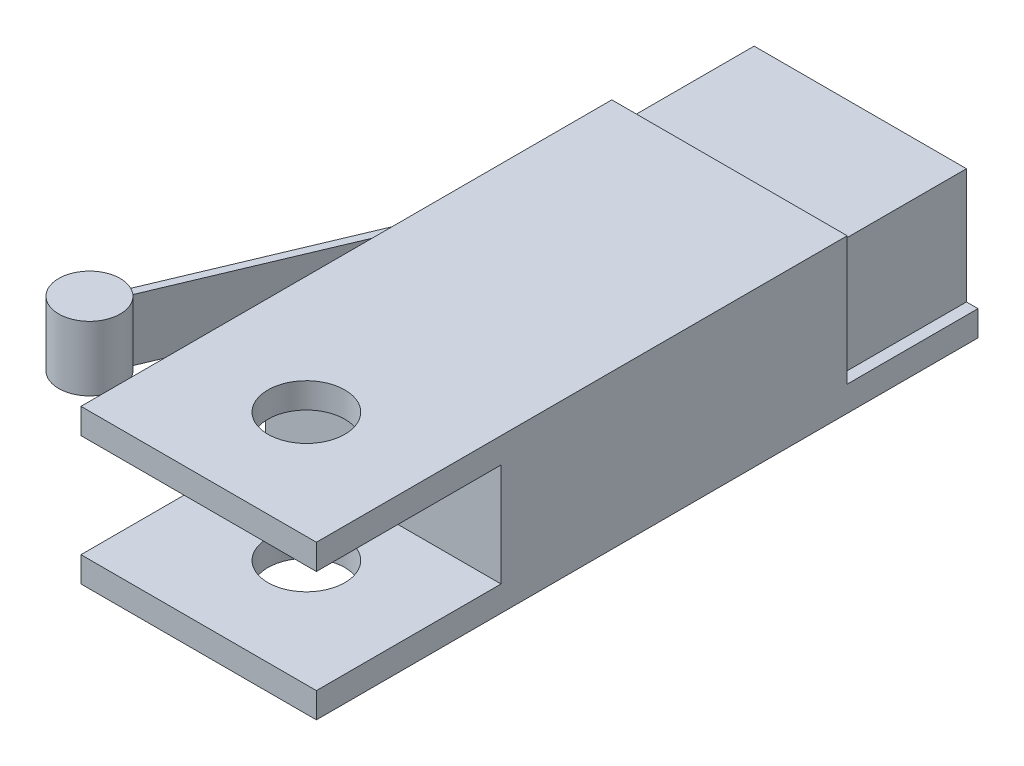
SolidWorks part; units mm, degrees
ref_plane "Front Plane" through (0, 0, 0) normal (0, 0, 1) x (1, 0, 0)
ref_plane "Top Plane" through (0, 0, 0) normal (0, 1, 0) x (1, 0, 0)
ref_plane "Right Plane" through (0, 0, 0) normal (1, 0, 0) x (0, 0, -1)
sketch "Sketch1" plane through (0, 0, 0) normal (0, 1, 0) x (1, 0, 0)
  line L1 (-7.65, 21.5) -> (7.65, 21.5)
  line L2 (-7.65, 21.5) -> (-7.65, -21.5)
  line L3 (-7.65, -21.5) -> (7.65, -21.5)
  line L4 (7.65, 21.5) -> (7.65, -21.5)
  line L5 (-7.65, 21.5) -> (7.65, -21.5) construction
  line L6 (-7.65, -21.5) -> (7.65, 21.5) construction
  point P0 (0, 0)
  dimension "D1" = 15.3
  dimension "D2" = 43
extrude "Boss-Extrude1" add sketch "Sketch1" along normal blind 10 contours L2 L3 L4 L1
sketch "Sketch2" plane through (7.65, 0, 0) normal (1, 0, 0) x (0, 0, -1)
  line L0 (-21.5, 10) -> (-21.5, 0) construction
  line L1 (-21.5, 8.35) -> (-9.5, 8.35)
  line L2 (-21.5, 8.35) -> (-21.5, 1.65)
  line L3 (-21.5, 1.65) -> (-9.5, 1.65)
  line L4 (-9.5, 8.35) -> (-9.5, 1.65)
  line L5 (21.5, 10) -> (-21.5, 10) construction
  line L6 (55, 0) -> (-55, 0) construction
  line L7 (21.5, 10) -> (21.5, 0) construction
  line L8 (13, 10) -> (21.5, 10)
  line L9 (13, 10) -> (13, 1.65)
  line L10 (13, 1.65) -> (21.5, 1.65)
  line L11 (21.5, 10) -> (21.5, 1.65)
  dimension "D1" = 1.65
  dimension "D2" = 1.65
  dimension "D3" = 1.65
  dimension "D4" = 34.5
  dimension "D5" = 12
extrude "Cut-Extrude1" cut sketch "Sketch2" against normal through all
sketch "Sketch3" plane through (0, 1.65, 0) normal (0, 1, 0) x (1, 0, 0)
  line L1 (-6.9, 21.5) -> (6.9, 21.5)
  line L2 (-6.9, 21.5) -> (-6.9, 13.5)
  line L3 (-6.9, 13.5) -> (6.9, 13.5)
  line L4 (6.9, 21.5) -> (6.9, 13.5)
  line L5 (-7.65, 21.5) -> (7.65, 21.5) construction
  line L6 (-7.65, 13) -> (-7.65, 21.5) construction
  line L7 (7.65, 13) -> (7.65, 21.5) construction
  dimension "D1" = 8
  dimension "D2" = 0.75
  dimension "D3" = 0.75
extrude "Boss-Extrude2" add sketch "Sketch3" along normal blind 7.5 separate body contours L4 L3 L2 L1
sketch "Sketch4" plane through (0, 0, -21.5) normal (0, 0, -1) x (-1, 0, 0)
  line L0 (-6.4, 1.65) -> (-6.4, 7.65)
  line L1 (6.9, 1.65) -> (-6.9, 1.65) construction
  line L2 (-6.4, 7.65) -> (-5.6, 7.65)
  line L3 (-5.6, 7.65) -> (-6.4, 8.65)
  line L4 (-6.4, 8.65) -> (-2.4667, 8.65)
  line L5 (-2.4667, 8.65) -> (-3.2667, 7.65)
  line L6 (-3.2667, 7.65) -> (-2.4667, 7.65)
  line L7 (-2.4667, 7.65) -> (-2.4667, 1.65)
  line L8 (7.65, 1.65) -> (-7.65, 1.65) construction
  line L9 (-2.4667, 1.65) -> (-6.4, 1.65)
  line L10 (-6.9, 9.15) -> (-6.9, 1.65) construction
  dimension "D1" = 0.5
  dimension "D2" = 3.9333
  dimension "D3" = 3.9333
  dimension "D4" = 0.8
  dimension "D5" = 0.8
  dimension "D6" = 7
  dimension "D7" = 6
extrude "Cut-Extrude2" cut sketch "Sketch4" against normal blind 7.5 contours L3 L4 L5 L6 L7 L9 L0 L2
pattern_linear "LPattern1" count 3 spacing 4.4333 along (-1, 0, 0) of "Cut-Extrude2"
ref_plane "Plane1" through (0, 3, 0) normal (0, 1, 0) x (1, 0, 0)
sketch "Sketch6" plane through (0, 3, 0) normal (0, 1, 0) x (1, 0, 0)
  line L0 (-6.7763, 10.9174) -> (-16.4718, -12.1259)
  line L1 (-16.4718, -12.1259) -> (-16.011, -12.3198)
  line L2 (-16.011, -12.3198) -> (-6.3155, 10.7235)
  line L3 (-6.3155, 10.7235) -> (-6.7763, 10.9174)
  dimension "D1" = 25
  dimension "D2" = 0.5
extrude "Boss-Extrude3" add sketch "Sketch6" along normal blind 4 separate body contours L0 L1 L2 L3
sketch "Sketch7" plane through (0, 3, 0) normal (0, 1, 0) x (1, 0, 0)
  circle A0 centre (-16.4718, -12.1259) radius 2
  dimension "D1" = 4
extrude "Boss-Extrude4" add sketch "Sketch7" along normal blind 4.1 and the other way blind 0.1 separate body
sketch "Sketch8" plane through (0, 0, 0) normal (0, -1, 0) x (1, 0, 0)
  line L0 (0, -5.5) -> (0, 5.5) construction
  line L1 (-7.65, 21.5) -> (7.65, 21.5) construction
  circle A0 centre (0, 14.5) radius 2.5
  dimension "D1" = 5
  dimension "D2" = 7
extrude "Cut-Extrude3" cut sketch "Sketch8" against normal through all contours A0
